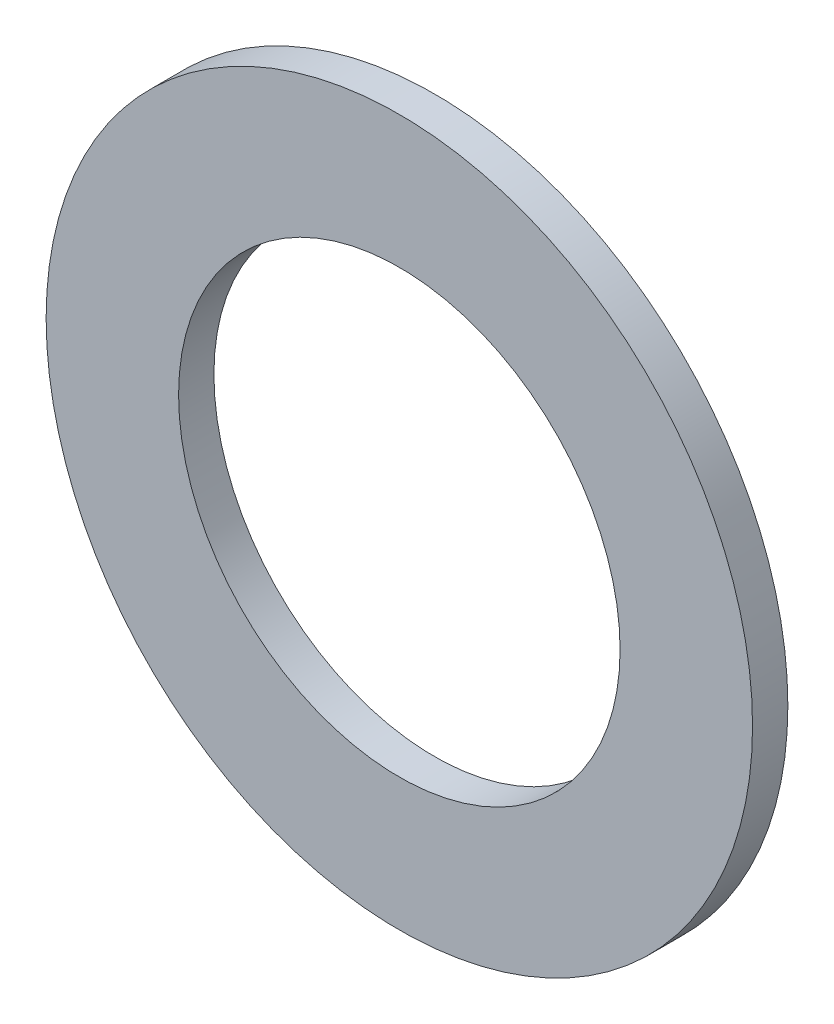
SolidWorks part; units mm, degrees
ref_plane "Plan1" through (0, 0, 0) normal (0, 0, 1) x (1, 0, 0)
ref_plane "Plan2" through (0, 0, 0) normal (0, 1, 0) x (1, 0, 0)
ref_plane "Plan3" through (0, 0, 0) normal (1, 0, 0) x (0, 0, -1)
sketch "Esquisse1" plane through (0, 0, 0) normal (0, 0, 1) x (1, 0, 0)
  circle A0 centre (0, 0) radius 40
  circle A1 centre (0, 0) radius 25
extrude "Base-Extrusion" add sketch "Esquisse1" along normal mid plane 4
